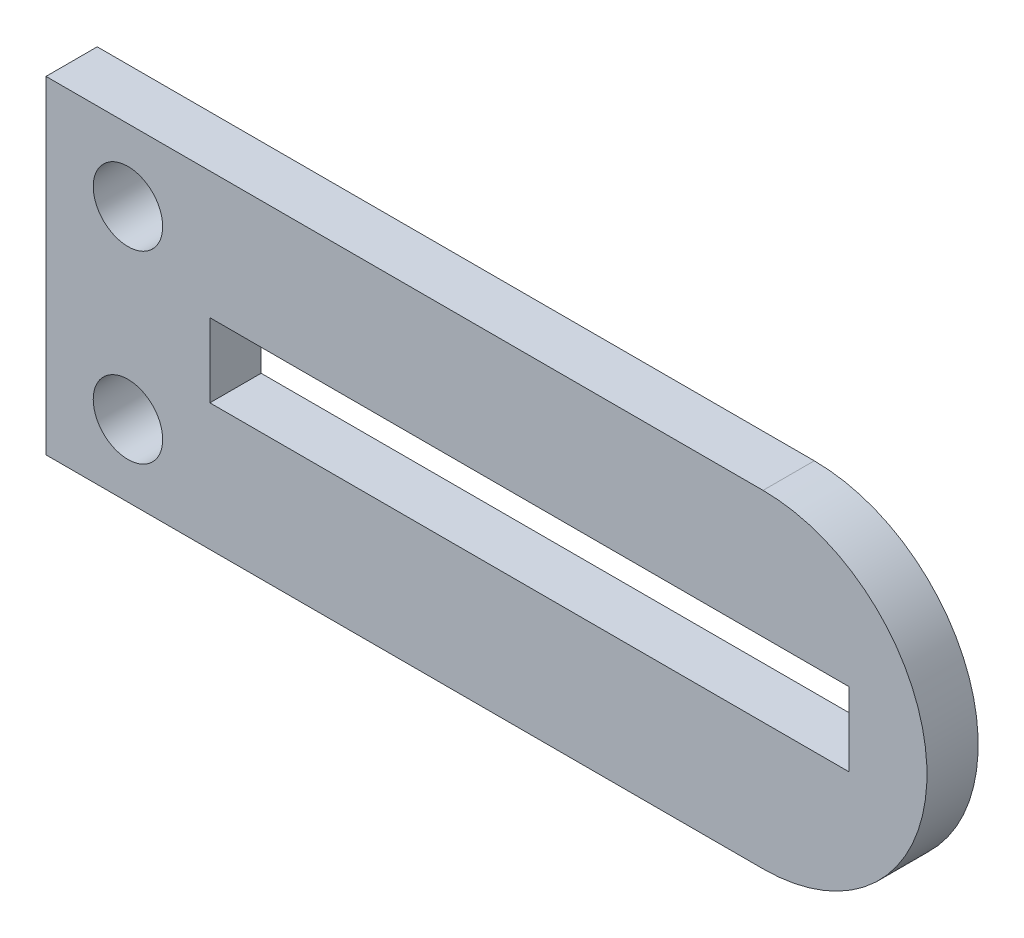
SolidWorks part; units mm, degrees
material "6061-T6 (SS)"
ref_plane "Front Plane" through (0, 0, 0) normal (0, 0, 1) x (1, 0, 0)
ref_plane "Top Plane" through (0, 0, 0) normal (0, 1, 0) x (1, 0, 0)
ref_plane "Right Plane" through (0, 0, 0) normal (1, 0, 0) x (0, 0, -1)
sketch "Sketch1" plane through (0, 0, 0) normal (0, 0, 1) x (1, 0, 0)
  line L0 (0, 0) -> (0, 20.32)
  line L1 (0, 20.32) -> (44.45, 20.32)
  line L3 (44.45, 0) -> (0, 0)
  line L4 (0, 10.16) -> (54.61, 10.16) construction
  line L5 (44.45, 20.32) -> (44.45, 0) construction
  line L6 (10.16, 7.874) -> (49.784, 7.874)
  line L7 (10.16, 7.874) -> (10.16, 12.446)
  line L8 (10.16, 12.446) -> (49.784, 12.446)
  line L9 (49.784, 7.874) -> (49.784, 12.446)
  line L10 (10.16, 7.874) -> (49.784, 12.446) construction
  line L11 (10.16, 12.446) -> (49.784, 7.874) construction
  arc A1 (44.45, 20.32) -> (44.45, 0) centre (44.45, 10.16) cw
  circle A2 centre (5.08, 15.875) radius 2.1526
  circle A3 centre (5.08, 4.445) radius 2.1526
  point P8 (29.972, 10.16)
  dimension "D3" = 54.61
  dimension "D5" = 10.16
  dimension "D7" = 5.715
  dimension "D8" = 4.3053
  dimension "D9" = 5.08
  dimension "D1" = 10.16
  dimension "D2" = 39.624
  dimension "D4" = 20.32
  dimension "D6" = 4.572
extrude "Boss-Extrude1" add sketch "Sketch1" along normal blind 3.175
